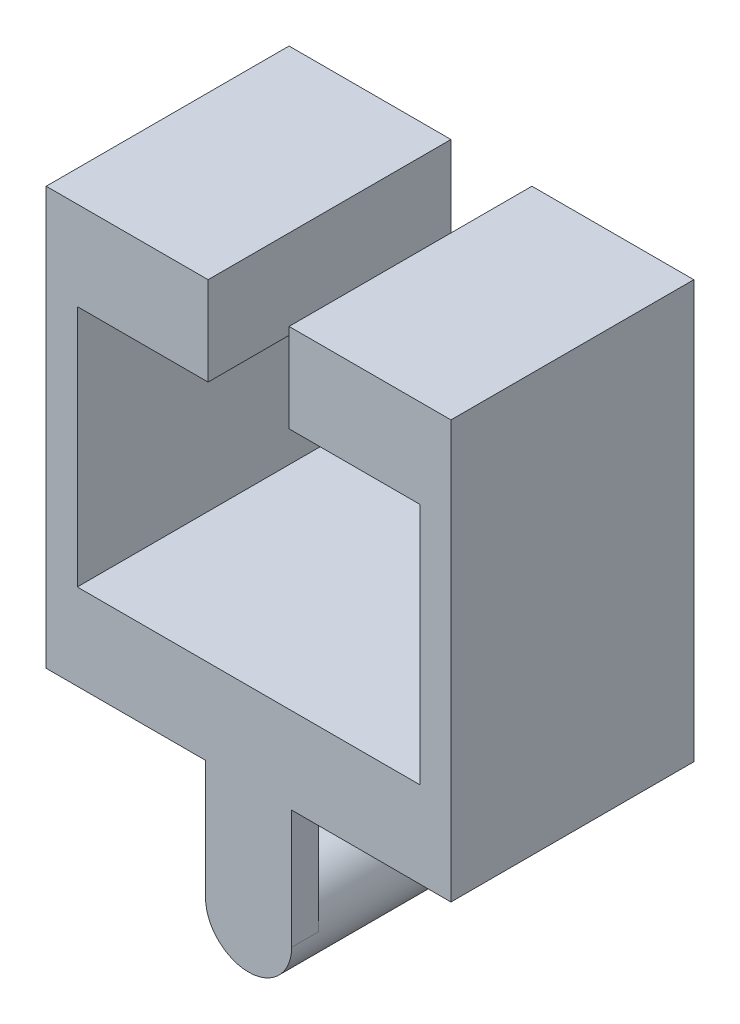
SolidWorks part; units mm, degrees
ref_plane "Front Plane" through (0, 0, 0) normal (0, 0, 1) x (1, 0, 0)
ref_plane "Top Plane" through (0, 0, 0) normal (0, 1, 0) x (1, 0, 0)
ref_plane "Right Plane" through (0, 0, 0) normal (1, 0, 0) x (0, 0, -1)
sketch "Sketch1" plane through (0, 0, 0) normal (0, 0, 1) x (1, 0, 0)
  circle A0 centre (0, 0) radius 6.7564
  dimension "D1" = 13.5128
extrude "Boss-Extrude2" add sketch "Sketch1" along normal blind 38.1 contours A0
sketch "Sketch2" plane through (0, 0, 38.1) normal (0, 0, 1) x (1, 0, 0)
  line L0 (-6.7564, 0) -> (6.7564, 0) construction
  line L1 (-6.7564, 0) -> (6.7564, 0)
  line L2 (6.7564, 0) -> (6.7564, 18.6436)
  line L3 (6.7564, 18.6436) -> (-6.7564, 18.6436)
  line L4 (-6.7564, 18.6436) -> (-6.7564, 0)
  circle A0 centre (0, 0) radius 6.7564 construction
  dimension "D1" = 18.6436
extrude "Boss-Extrude3" add sketch "Sketch2" against normal blind 4.2393 contours L3 L4 L1 L2
sketch "Sketch4" plane through (0, 18.6436, 0) normal (0, 1, 0) x (1, 0, 0)
  line L0 (0, -38.1) -> (-31.75, -38.1)
  line L1 (6.7564, -38.1) -> (-6.7564, -38.1) construction
  line L2 (0, -38.1) -> (31.75, -38.1)
  line L3 (-31.75, -38.1) -> (-31.75, 0)
  line L4 (-31.75, 0) -> (31.75, 0)
  line L5 (31.75, 0) -> (31.75, -38.1)
extrude "Boss-Extrude6" add sketch "Sketch4" along normal blind 13.495
sketch "Sketch7" plane through (0, 32.1386, 0) normal (0, 1, 0) x (1, 0, 0)
  line L0 (-31.75, 0) -> (-31.75, -38.1)
  line L1 (-31.75, 0) -> (-31.75, -38.1) construction
  line L2 (-31.75, -38.1) -> (-26.8732, -38.1)
  line L3 (-31.75, -38.1) -> (31.75, -38.1) construction
  line L4 (-26.8732, -38.1) -> (-26.8732, 0)
  line L5 (31.75, 0) -> (-31.75, 0) construction
  line L6 (-26.8732, 0) -> (-31.75, 0)
  line L7 (31.75, 0) -> (31.75, -38.1)
  line L8 (31.75, -38.1) -> (26.8732, -38.1)
  line L9 (26.8732, -38.1) -> (26.8732, 0)
  line L10 (26.8732, 0) -> (31.75, 0)
extrude "Boss-Extrude10" add sketch "Sketch7" along normal blind 38.1
sketch "Sketch8" plane through (0, 70.2386, 0) normal (0, 1, 0) x (1, 0, 0)
  line L0 (-31.75, 0) -> (-6.35, 0)
  line L1 (26.8732, 0) -> (-26.8732, 0) construction
  line L2 (-31.75, 0) -> (-31.75, -38.1)
  line L3 (-31.75, -38.1) -> (-6.35, -38.1)
  line L4 (-26.8732, -38.1) -> (26.8732, -38.1) construction
  line L5 (-6.35, -38.1) -> (-6.35, 0)
  line L6 (31.75, 0) -> (31.75, -38.1)
  line L7 (31.75, -38.1) -> (6.35, -38.1)
  line L8 (6.35, -38.1) -> (6.35, 0)
  line L9 (6.35, 0) -> (31.75, 0)
extrude "Boss-Extrude11" add sketch "Sketch8" along normal blind 13.9116
